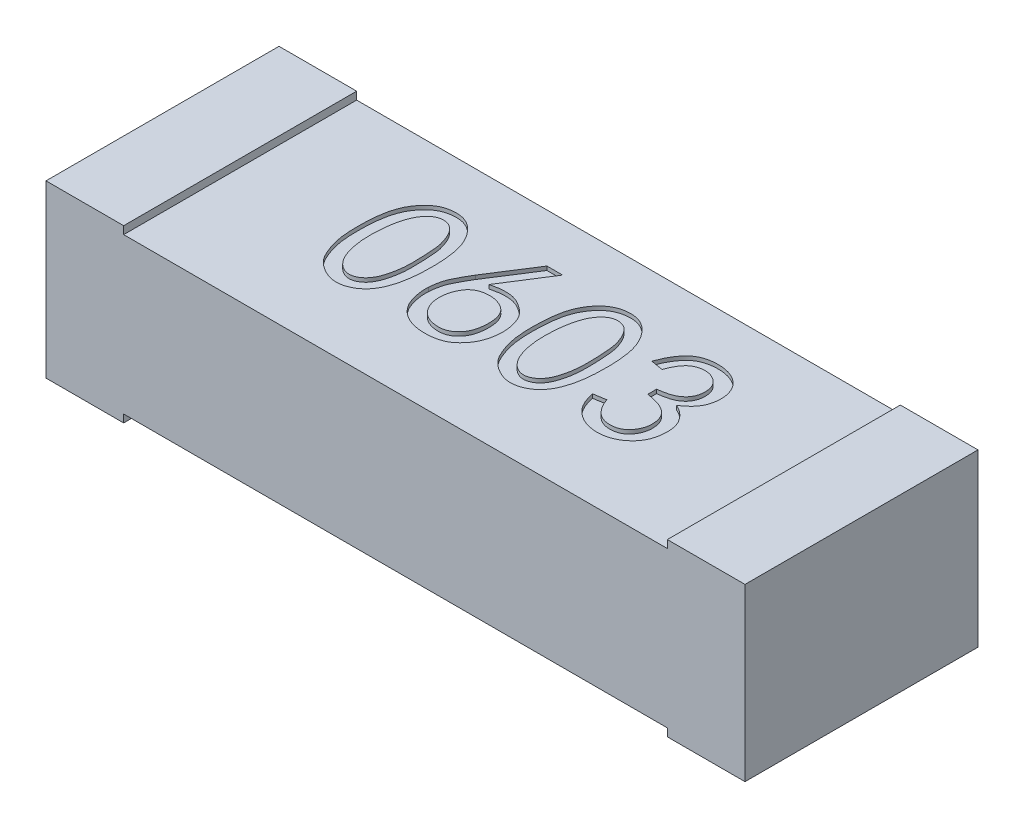
SolidWorks part; units mm, degrees
ref_plane "前视基准面" through (0, 0, 0) normal (0, 0, 1) x (1, 0, 0)
ref_plane "上视基准面" through (0, 0, 0) normal (0, 1, 0) x (1, 0, 0)
ref_plane "右视基准面" through (0, 0, 0) normal (1, 0, 0) x (0, 0, -1)
sketch "草图1" plane through (0, 0, 0) normal (0, 1, 0) x (1, 0, 0)
  line L0 (0.2, 0.6) -> (0.2, 0)
  line L1 (0.2, 0) -> (1.6, 0)
  line L2 (0, 0) -> (0, 0.6) construction
  line L3 (0.2, 0.6) -> (1.6, 0.6)
  line L4 (1.8, 0) -> (1.8, 0.6) construction
  line L5 (1.6, 0.6) -> (1.6, 0)
  dimension "D3" = 0.2
  dimension "D4" = 0.2
  dimension "D5" = 1.8
  dimension "D6" = 0.6
extrude "凸台-拉伸1" add sketch "草图1" along normal blind 0.4
sketch "草图3" plane through (0, 0, 0) normal (0, 1, 0) x (1, 0, 0)
  line L1 (0, 0) -> (0.2, 0)
  line L2 (0, 0) -> (0, 0.6)
  line L3 (0, 0.6) -> (0.2, 0.6)
  line L4 (0.2, 0) -> (0.2, 0.6)
  line L5 (1.6, 0.6) -> (1.8, 0.6)
  line L6 (1.6, 0.6) -> (1.6, 0)
  line L7 (1.6, 0) -> (1.8, 0)
  line L8 (1.8, 0.6) -> (1.8, 0)
  line L9 (0.2, 0) -> (1.6, 0) construction
extrude "凸台-拉伸2" add sketch "草图3" along normal blind 0.42 and the other way blind 0.02
sketch "草图4" plane through (0, 0.4, 0) normal (0, 1, 0) x (1, 0, 0)
  text T0 "0603" font "黑体" height 0.3
extrude "切除-拉伸1" cut sketch "草图4" against normal blind 0.01
